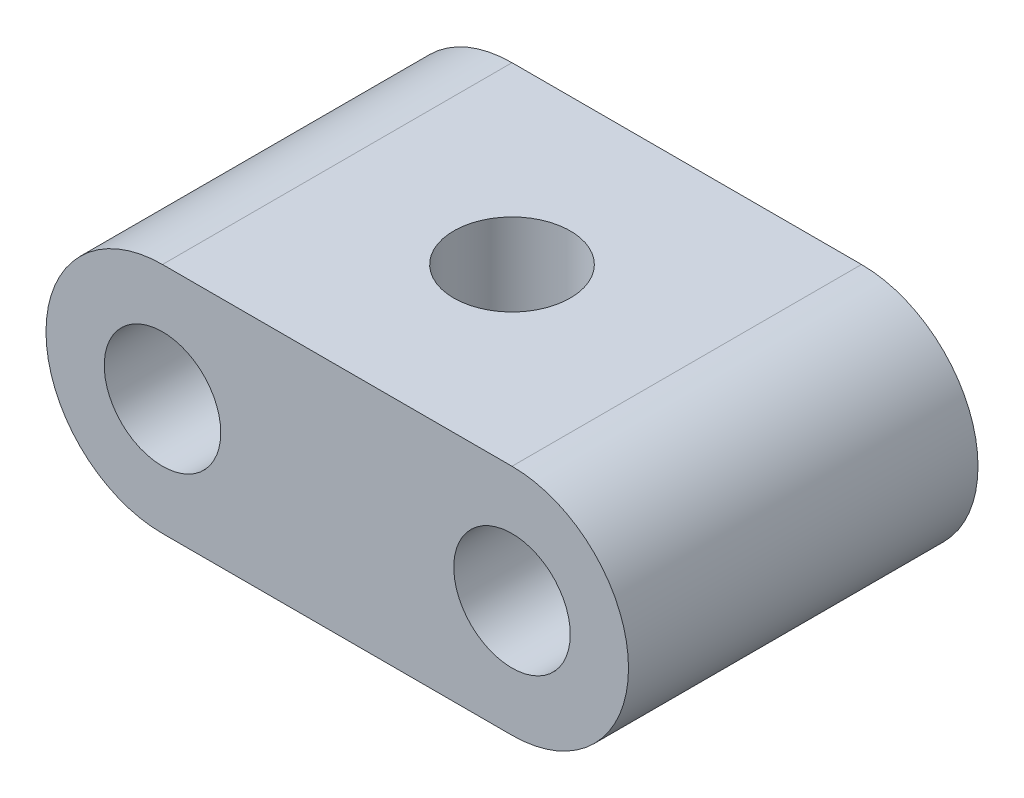
SolidWorks part; units mm, degrees
ref_plane "Ön Düzlem" through (0, 0, 0) normal (0, 0, 1) x (1, 0, 0)
ref_plane "Üst Düzlem" through (0, 0, 0) normal (0, 1, 0) x (1, 0, 0)
ref_plane "Sağ Düzlem" through (0, 0, 0) normal (1, 0, 0) x (0, 0, -1)
sketch "Çizim2" plane through (0, 0, 0) normal (0, 0, 1) x (1, 0, 0)
  line L0 (-37.4994, 24.0081) -> (-7.4994, 24.0081) construction
  line L1 (-37.4994, 34.0081) -> (-7.4994, 34.0081)
  line L2 (-37.4994, 14.0081) -> (-7.4994, 14.0081)
  arc A0 (-37.4994, 34.0081) -> (-37.4994, 14.0081) centre (-37.4994, 24.0081) ccw
  arc A1 (-7.4994, 14.0081) -> (-7.4994, 34.0081) centre (-7.4994, 24.0081) ccw
  circle A2 centre (-37.4994, 24.0081) radius 5
  circle A3 centre (-7.4994, 24.0081) radius 5
  point P2 (-22.4994, 24.0081)
extrude "Yükseklik-Ekstrüzyon1" add sketch "Çizim2" along normal blind 30
sketch "Çizim3" plane through (0, 34.0081, 0) normal (0, 1, 0) x (1, 0, 0)
  circle A0 centre (-22.4994, -15) radius 5
extrude "Kes-Ekstrüzyon1" cut sketch "Çizim3" against normal blind 20 contours A0
